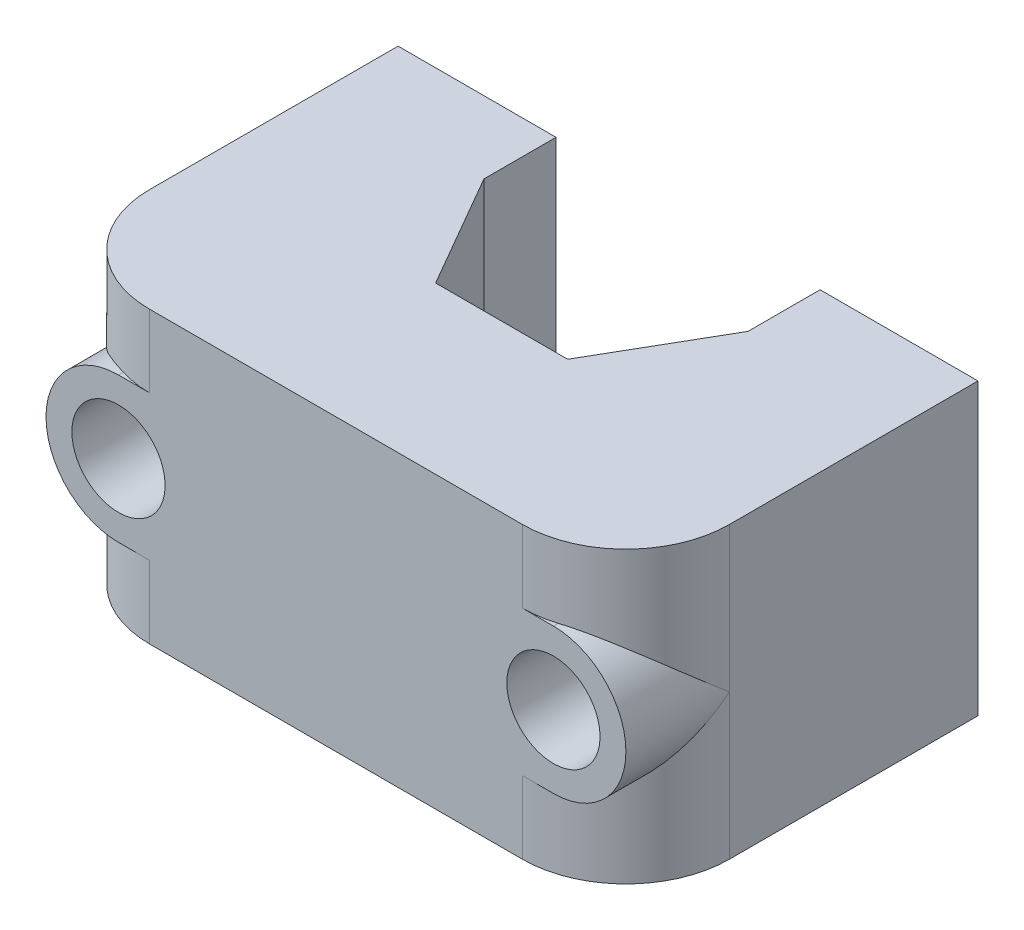
SolidWorks part; units mm, degrees
other "Markup1"
sketch "Sketch7" plane through (-25, 28, 17) normal (-0.0337, 0.6437, 0.7645) x (0.9929, 0.1091, -0.048)
ref_plane "Front" through (0, 0, 0) normal (0, 0, 1) x (1, 0, 0)
ref_plane "Top" through (0, 0, 0) normal (0, 1, 0) x (1, 0, 0)
ref_plane "Right" through (0, 0, 0) normal (1, 0, 0) x (0, 0, -1)
sketch "Sketch1" plane through (0, 0, 0) normal (0, 1, 0) x (1, 0, 0)
  line L1 (-28, -17) -> (28, -17)
  line L2 (-28, -17) -> (-28, 17)
  line L3 (-28, 17) -> (28, 17)
  line L4 (28, -17) -> (28, 17)
  line L5 (-28, -17) -> (28, 17) construction
  line L6 (-28, 17) -> (28, -17) construction
  point P0 (0, 0)
  dimension "D1" = 56
  dimension "D2" = 34
extrude "Boss-Extrude1" add sketch "Sketch1" along normal blind 28
sketch "Sketch2" plane through (0, 28, 0) normal (0, 1, 0) x (1, 0, 0)
  line L3 (-12.75, 10.0418) -> (-6.375, -1)
  line L4 (-6.375, -1) -> (6.375, -1)
  line L5 (6.375, -1) -> (12.75, 10.0418)
  line L9 (-12.75, 10.0418) -> (-12.75, 17)
  line L10 (28, 17) -> (-28, 17) construction
  line L11 (12.75, 10.0418) -> (12.75, 17)
  line L12 (-12.75, 17) -> (12.75, 17)
  line L14 (-3.2982, 26.4129) -> (-7.4732, 19.1816) [skipped]
  line L15 (15.8268, 4.7126) -> (11.6518, 11.9439) [skipped]
  line L16 (12.5287, 21.0836) -> (-4.1713, 21.0836) [skipped]
  arc A0 (-8.4457, 2.5865) -> (8.4457, 2.5865) centre (0, 10.0418) ccw construction
  dimension "D1" = 12.75
  dimension "D2" = 18
extrude "Cut-Extrude1" cut sketch "Sketch2" against normal blind 18.6
sketch "Sketch3" plane through (0, 9.4, 0) normal (0, 1, 0) x (1, 0, 0)
  line L0 (-11, 10) -> (-11, 17)
  line L1 (12.75, 17) -> (-12.75, 17) construction
  line L2 (11, 10) -> (11, 17)
  line L3 (-11, 17) -> (11, 17)
  line L4 (-6.375, -1) -> (6.375, -1) construction
  arc A0 (-11, 10) -> (11, 10) centre (0, 10) ccw
  point P1 (0, -1)
  dimension "D1" = 22
extrude "Cut-Extrude2" cut sketch "Sketch3" against normal up to surface (9.4 mm away) up to face at (0, 0, 0)
fillet "Fillet1" radius 10 2 edges at (28, 14, 17) (-28, 14, 17)
sketch "Sketch5" plane through (0, 0, 1) normal (0, 0, -1) x (-1, 0, 0)
  line L0 (18, 21) -> (18, 7)
  line L1 (18, 28) -> (18, 0) construction
  line L2 (-18, 14) -> (18, 14) construction
  line L3 (-18, 0) -> (-18, 28) construction
  line L4 (18, 21) -> (21, 21)
  line L5 (18, 7) -> (21, 7)
  line L6 (28, 0) -> (28, 28) construction
  line L7 (0, 50) -> (0, -50) construction
  line L8 (-18, 7) -> (-21, 7)
  line L9 (-18, 21) -> (-18, 7)
  line L10 (-18, 21) -> (-21, 21)
  arc A1 (21, 21) -> (21, 7) centre (21, 14) cw
  arc A2 (-21, 21) -> (-21, 7) centre (-21, 14) ccw
  point P6 (28, 14)
  point P14 (28, 14)
  dimension "D1" = 14
extrude "Boss-Extrude2" add sketch "Sketch5" against normal up to surface (16 mm away) up to face at (0, 14, 17)
sketch "Sketch6" plane through (0, 0, 17) normal (0, 0, 1) x (1, 0, 0)
  line L0 (-28, 14) -> (-28, 28) construction
  circle A0 centre (-21, 14) radius 2.875
  circle A1 centre (21, 14) radius 2.875
  dimension "D1" = 5.75
  dimension "D2" = 7
extrude "Cut-Extrude3" cut sketch "Sketch6" against normal up to surface (34 mm away) up to face at (-17.25, 12.4667, -17)
ref_plane "Plane1" through (0, 0, -7) normal (0, 0, -1) x (-1, 0, 0)
sketch "Sketch8" plane through (0, 0, -7) normal (0, 0, -1) x (-1, 0, 0)
  circle A0 centre (21, 14) radius 4.5
  circle A1 centre (-21, 14) radius 4.5
  dimension "D1" = 9
extrude "Cut-Extrude4" cut sketch "Sketch8" against normal up to surface (24 mm away) up to face at (-18.125, 14, 17)
